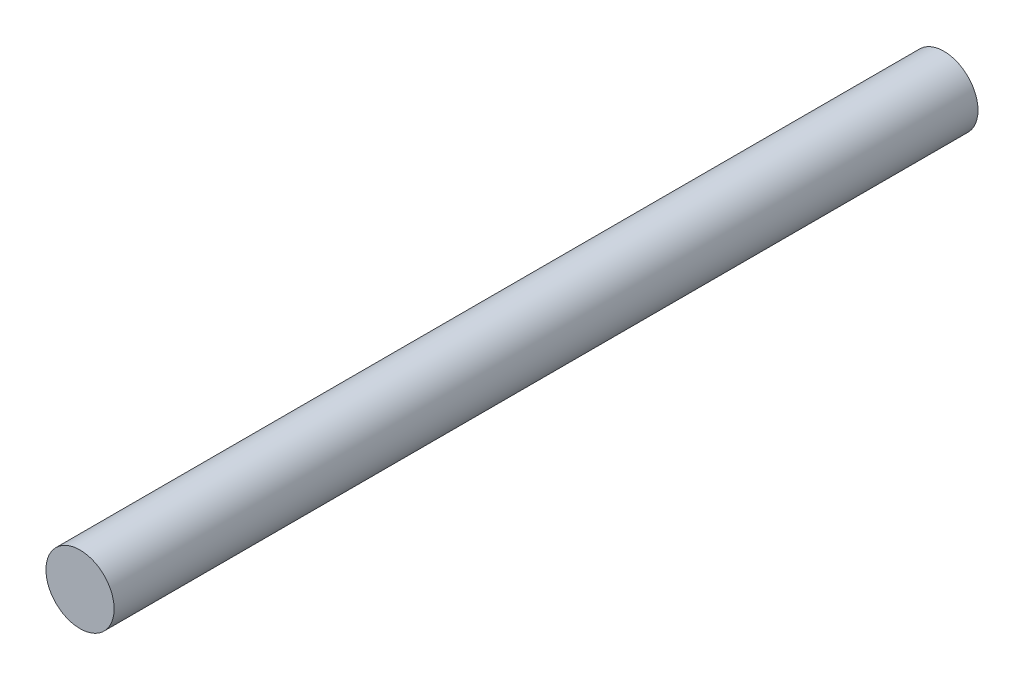
SolidWorks part; units mm, degrees
material "AISI 304"
ref_plane "前视基准面" through (0, 0, 0) normal (0, 0, 1) x (1, 0, 0)
ref_plane "上视基准面" through (0, 0, 0) normal (0, 1, 0) x (1, 0, 0)
ref_plane "右视基准面" through (0, 0, 0) normal (1, 0, 0) x (0, 0, -1)
sketch "草图1" plane through (0, 0, 0) normal (0, 0, 1) x (1, 0, 0)
  circle A0 centre (0, 0) radius 1.5
  dimension "D1" = 3
extrude "凸台-拉伸1" add sketch "草图1" along normal blind 38
